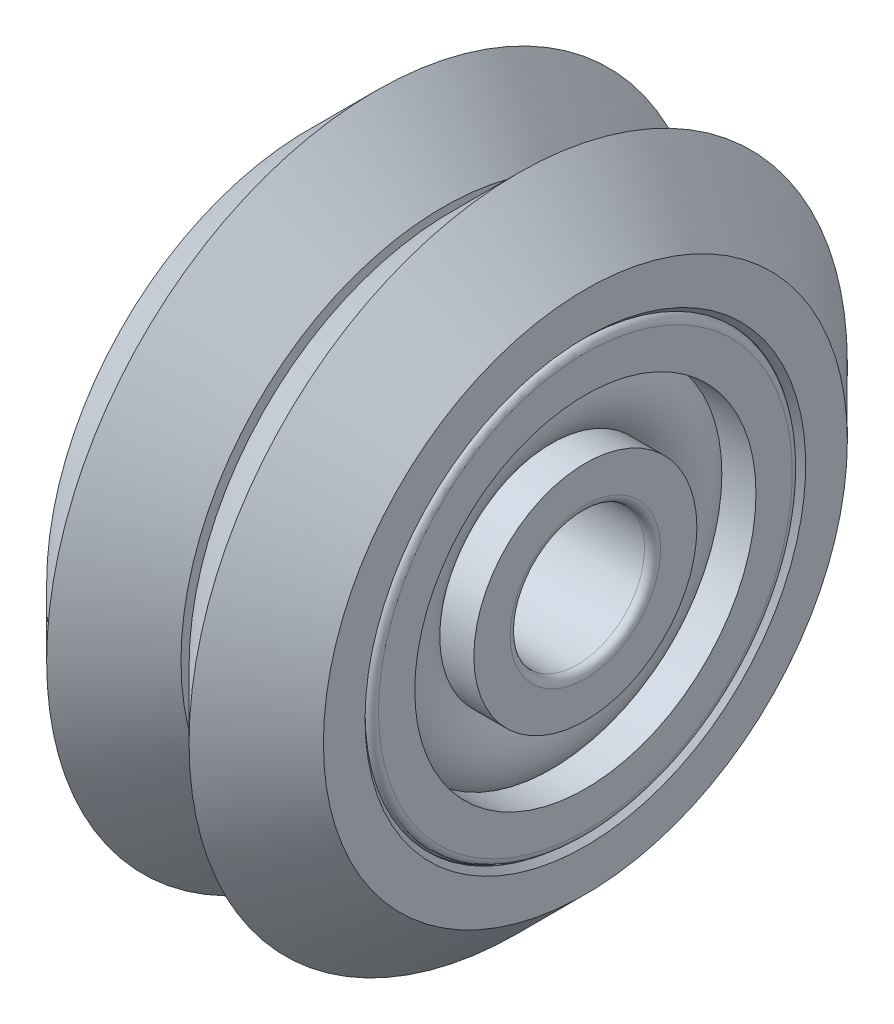
SolidWorks part; units mm, degrees
material "Silicon Rubber"
ref_plane "Plano frontal" through (0, 0, 0) normal (0, 0, 1) x (1, 0, 0)
ref_plane "Plano superior" through (0, 0, 0) normal (0, 1, 0) x (1, 0, 0)
ref_plane "Plano direito" through (0, 0, 0) normal (1, 0, 0) x (0, 0, -1)
ref_plane "Plane2" through (0, 0, 0) normal (0, 0, -1) x (-1, 0, 0)
sketch "Sketch14" plane through (0, 0, 0) normal (0, 0, -1) x (-1, 0, 0)
  line L0 (-0.15, 2.8) -> (-0.15, 4.15)
  line L1 (-0.15, 4.15) -> (-1.4202, 4.15)
  line L2 (-1.4202, 6.35) -> (-0.15, 6.35)
  line L3 (-0.15, 6.35) -> (-0.15, 7.7)
  line L4 (-0.45, 8) -> (-4.85, 8)
  line L5 (-5.15, 7.7) -> (-5.15, 6.35)
  line L6 (-5.15, 6.35) -> (-3.8798, 6.35)
  line L7 (-3.8798, 4.15) -> (-5.15, 4.15)
  line L8 (-5.15, 4.15) -> (-5.15, 2.8)
  line L9 (-4.85, 2.5) -> (-0.45, 2.5)
  line L10 (-5.1669, 0) -> (-0.1331, 0) construction
  arc A0 (-0.15, 2.8) -> (-0.45, 2.5) centre (-0.45, 2.8) cw
  arc A1 (-1.4202, 6.35) -> (-1.4202, 4.15) centre (-2.65, 5.25) cw
  arc A2 (-0.45, 8) -> (-0.15, 7.7) centre (-0.45, 7.7) cw
  arc A3 (-5.15, 7.7) -> (-4.85, 8) centre (-4.85, 7.7) cw
  arc A4 (-3.8798, 4.15) -> (-3.8798, 6.35) centre (-2.65, 5.25) cw
  arc A5 (-4.85, 2.5) -> (-5.15, 2.8) centre (-4.85, 2.8) cw
revolve "Revolve4" add sketch "Sketch14" angle 360 about L10
sketch "Sketch16" plane through (0, 0, 0) normal (0, 0, 1) x (1, 0, 0)
  line L0 (-0.15, 2.8) -> (-0.15, 4.15)
  line L1 (-0.15, 4.15) -> (-1.4202, 4.15)
  line L2 (-1.4202, 6.35) -> (-0.15, 6.35)
  line L3 (-0.15, 6.35) -> (-0.15, 7.7)
  line L4 (-0.45, 8) -> (-4.85, 8)
  line L5 (-5.15, 7.7) -> (-5.15, 6.35)
  line L6 (-5.15, 6.35) -> (-3.8798, 6.35)
  line L7 (-3.8798, 4.15) -> (-5.15, 4.15)
  line L8 (-5.15, 4.15) -> (-5.15, 2.8)
  line L9 (-4.85, 2.5) -> (-0.45, 2.5)
  line L10 (-5.1669, 0) -> (-0.1331, 0) construction
  arc A0 (-0.15, 2.8) -> (-0.45, 2.5) centre (-0.45, 2.8) cw
  arc A1 (-1.4202, 6.35) -> (-1.4202, 4.15) centre (-2.65, 5.25) cw
  arc A2 (-0.45, 8) -> (-0.15, 7.7) centre (-0.45, 7.7) cw
  arc A3 (-5.15, 7.7) -> (-4.85, 8) centre (-4.85, 7.7) cw
  arc A4 (-3.8798, 4.15) -> (-3.8798, 6.35) centre (-2.65, 5.25) cw
  arc A5 (-4.85, 2.5) -> (-5.15, 2.8) centre (-4.85, 2.8) cw
revolve "Revolve5" add sketch "Sketch16" angle 360 about L10
sketch "Sketch21" plane through (0, 0, 0) normal (0, 0, -1) x (-1, 0, 0)
  line L0 (5.15, 8.2) -> (5.15, 9.75)
  line L1 (5.15, 9.75) -> (2.65, 12.25)
  line L2 (2.65, 12.25) -> (0.15, 9.75)
  line L3 (0.15, 9.75) -> (0.15, 9.25)
  line L4 (0.15, 9.25) -> (-0.15, 9.25)
  line L5 (-0.15, 9.25) -> (-0.15, 9.75)
  line L6 (-0.15, 9.75) -> (-2.65, 12.25)
  line L7 (-2.65, 12.25) -> (-5.15, 9.75)
  line L8 (-5.15, 9.75) -> (-5.15, 8.2)
  line L9 (-5.15, 8.2) -> (-4.95, 8)
  line L10 (-4.95, 8) -> (-0.15, 8)
  line L11 (-0.15, 8) -> (-0.15, 6.8)
  line L12 (-0.15, 6.8) -> (0.15, 6.8)
  line L13 (0.15, 6.8) -> (0.15, 8)
  line L14 (0.15, 8) -> (4.95, 8)
  line L15 (4.95, 8) -> (5.15, 8.2)
  line L16 (-5.15, 0) -> (5.15, 0) construction
revolve "Revolve6" add sketch "Sketch21" angle 360 about L16
